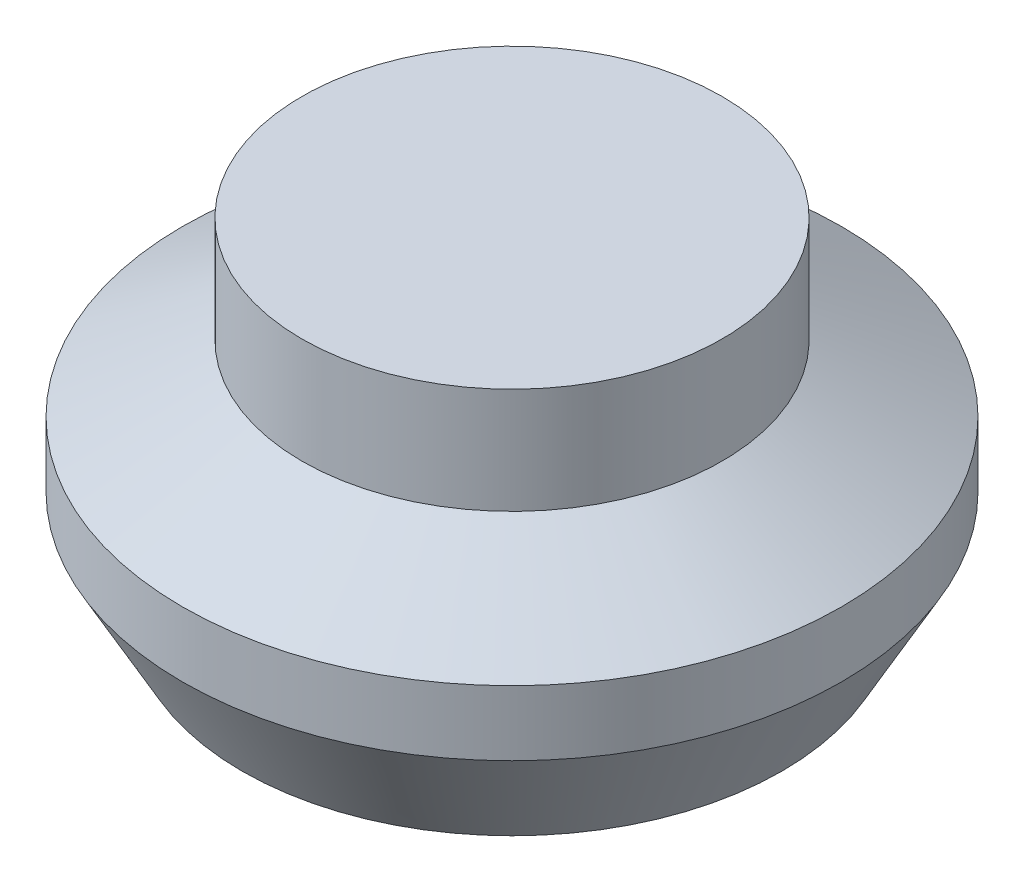
SolidWorks part; units mm, degrees
ref_plane "Front Plane" through (0, 0, 0) normal (0, 0, 1) x (1, 0, 0)
ref_plane "Top Plane" through (0, 0, 0) normal (0, 1, 0) x (1, 0, 0)
ref_plane "Right Plane" through (0, 0, 0) normal (1, 0, 0) x (0, 0, -1)
sketch "Sketch1" plane through (0, 0, 0) normal (0, 0, 1) x (1, 0, 0)
  line L0 (0, 0) -> (0, 46.9909) construction
  line L1 (0, 36.8351) -> (22.4073, 36.8351)
  line L2 (22.4073, 36.8351) -> (22.4073, 25.5508)
  line L3 (22.4073, 25.5508) -> (35.1424, 18.4578)
  line L4 (35.1424, 18.4578) -> (35.1424, 11.5261)
  line L5 (35.1424, 11.5261) -> (28.7749, 0.0934)
  line L6 (28.7749, 0.0934) -> (14.0247, 0.0934)
  line L7 (14.0247, 0.0934) -> (0, -17.6518)
  line L8 (0, -17.6518) -> (0, 36.8351)
revolve "Revolve1" add sketch "Sketch1" angle 360 about L0
